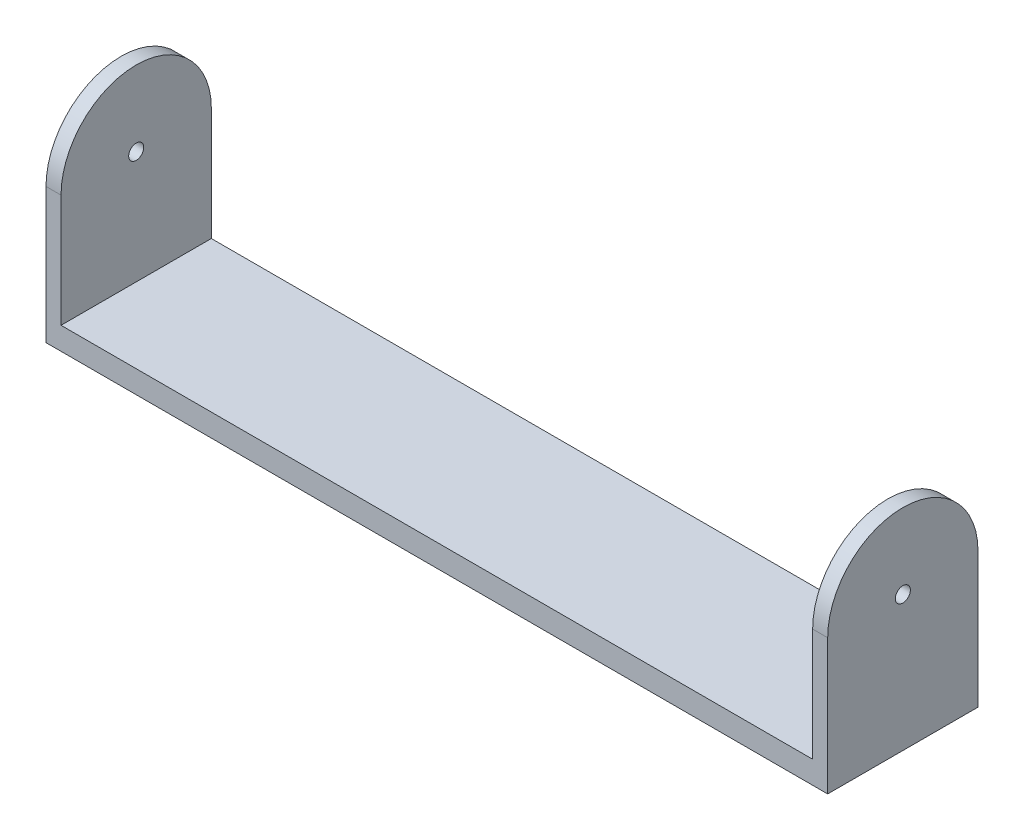
SolidWorks part; units mm, degrees
ref_plane "Front Plane" through (0, 0, 0) normal (0, 0, 1) x (1, 0, 0)
ref_plane "Top Plane" through (0, 0, 0) normal (0, 1, 0) x (1, 0, 0)
ref_plane "Right Plane" through (0, 0, 0) normal (1, 0, 0) x (0, 0, -1)
sketch "Sketch1" plane through (0, 0, 0) normal (0, 0, 1) x (1, 0, 0)
  line L1 (0, 0) -> (1040, 0)
  line L2 (0, 0) -> (0, -30)
  line L3 (0, -30) -> (1040, -30)
  line L4 (1040, 0) -> (1040, -30)
  dimension "D1" = 1040
  dimension "D2" = 30
extrude "Boss-Extrude1" add sketch "Sketch1" along normal blind 200
sketch "Sketch2" plane through (1040, 0, 0) normal (1, 0, 0) x (0, 0, -1)
  line L2 (-200, 0) -> (-200, 150)
  line L3 (0, 150) -> (0, 0)
  line L4 (0, 150) -> (-100, 150) construction
  line L5 (-100, 150) -> (-200, 150) construction
  line L6 (0, 0) -> (-200, 0)
  arc A1 (-200, 150) -> (0, 150) centre (-100, 150) cw
  dimension "D1" = 150
ref_plane "Plane1" through (520, 0, 0) normal (1, 0, 0) x (0, 0, -1)
extrude "Boss-Extrude3" add sketch "Sketch2" against normal blind 20
mirror "Mirror2" about plane through (520, 0, 0) normal (1, 0, 0) of "Boss-Extrude3"
sketch "Sketch3" plane through (20, 0, 0) normal (1, 0, 0) x (0, 0, -1)
  circle A0 centre (-100, 150) radius 10
  arc A1 (0, 150) -> (-200, 150) centre (-100, 150) ccw construction
  point P6 (-100, 250)
  dimension "D1" = 20
extrude "Cut-Extrude1" cut sketch "Sketch3" against normal through all both and the other way through all contours A0
sketch "Sketch4" plane through (520, 0, 0) normal (1, 0, 0) x (0, 0, -1)
